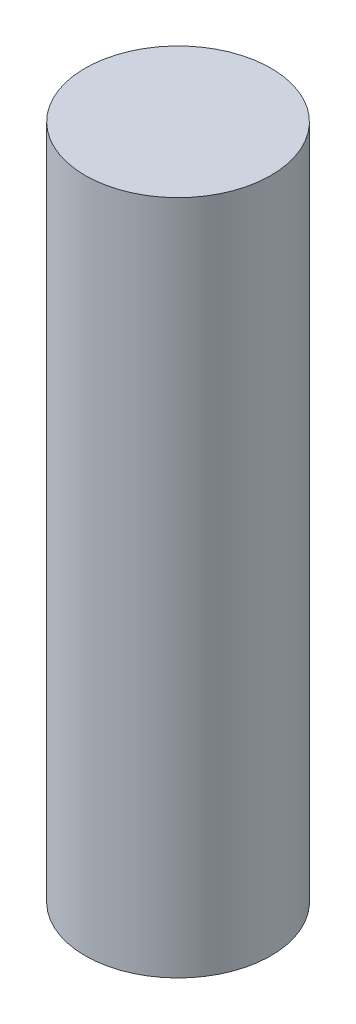
SolidWorks part; units mm, degrees
ref_plane "Front Plane" through (0, 0, 0) normal (0, 0, 1) x (1, 0, 0)
ref_plane "Top Plane" through (0, 0, 0) normal (0, 1, 0) x (1, 0, 0)
ref_plane "Right Plane" through (0, 0, 0) normal (1, 0, 0) x (0, 0, -1)
sketch "Sketch2" plane through (0, 0, 0) normal (0, 1, 0) x (1, 0, 0)
  circle A0 centre (0, 0) radius 27.5
extrude "Boss-Extrude1" add sketch "Sketch2" along normal mid plane 200
